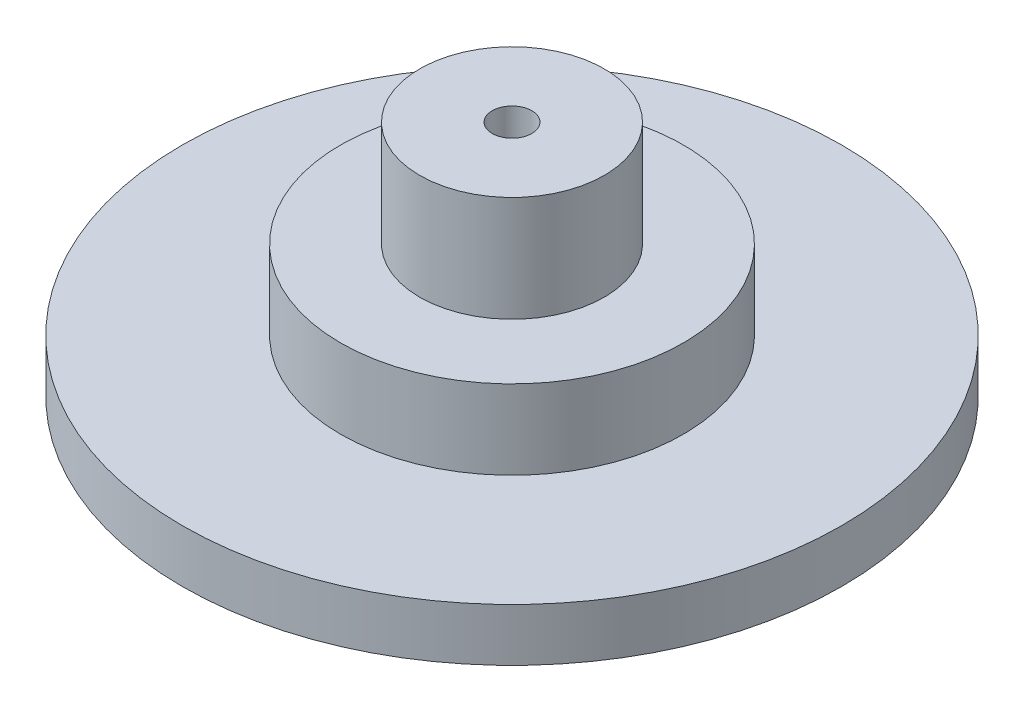
SolidWorks part; units mm, degrees
ref_plane "Front Plane" through (0, 0, 0) normal (0, 0, 1) x (1, 0, 0)
ref_plane "Top Plane" through (0, 0, 0) normal (0, 1, 0) x (1, 0, 0)
ref_plane "Right Plane" through (0, 0, 0) normal (1, 0, 0) x (0, 0, -1)
sketch "Sketch1" plane through (0, 0, 0) normal (0, 1, 0) x (1, 0, 0)
  circle A0 centre (0, 0) radius 25
  dimension "D1" = 50
extrude "Boss-Extrude1" add sketch "Sketch1" along normal blind 4
sketch "Sketch2" plane through (0, 4, 0) normal (0, 1, 0) x (1, 0, 0)
  circle A0 centre (0, 0) radius 13
  dimension "D1" = 26
extrude "Boss-Extrude2" add sketch "Sketch2" along normal blind 6
sketch "Sketch3" plane through (0, 10, 0) normal (0, 1, 0) x (1, 0, 0)
  circle A0 centre (0, 0) radius 7
  dimension "D1" = 14
extrude "Boss-Extrude3" add sketch "Sketch3" along normal blind 8 contours A0
sketch "Sketch4" plane through (0, 18, 0) normal (0, 1, 0) x (1, 0, 0)
  circle A0 centre (0, 0) radius 1.5
  dimension "D1" = 3
extrude "Cut-Extrude1" cut sketch "Sketch4" against normal through all
